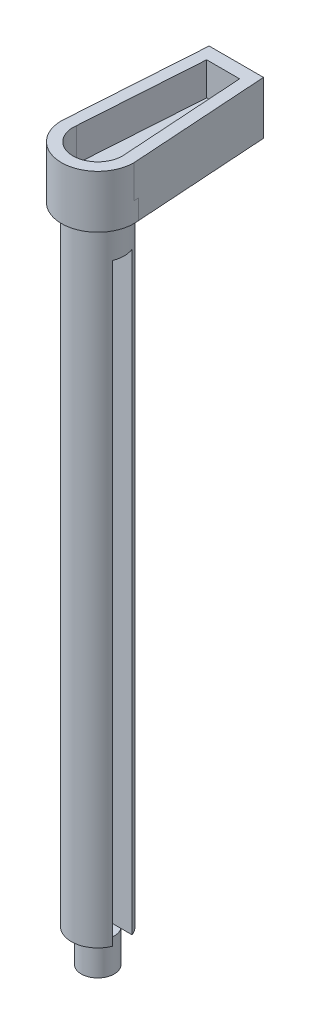
SolidWorks part; units mm, degrees
ref_plane "Front Plane" through (0, 0, 0) normal (0, 0, 1) x (1, 0, 0)
ref_plane "Top Plane" through (0, 0, 0) normal (0, 1, 0) x (1, 0, 0)
ref_plane "Right Plane" through (0, 0, 0) normal (1, 0, 0) x (0, 0, -1)
sketch "Sketch2" plane through (0, 0, 0) normal (0, 0, 1) x (1, 0, 0)
  line L0 (-25, 45) -> (-25, -45)
  line L1 (-25, -45) -> (25, -45)
  line L2 (25, -45) -> (25, 45)
  line L3 (25, 45) -> (-25, 45)
  line L4 (0, 0) -> (0, -45) construction
  line L5 (0, 0) -> (-25, 0) construction
  dimension "D1" = 50
  dimension "D2" = 90
extrude "Boss-Extrude1" add sketch "Sketch2" along normal mid plane 3
sketch "Sketch3" plane through (0, 0, 0) normal (0, -1, 0) x (1, 0, 0)
  line L0 (-25, 1.5) -> (-25, -1.5) construction
  circle A0 centre (-25, 0) radius 4
  point P2 (0, 0)
  point P3 (-26.0976, 0)
  point P4 (0, 0)
  point P5 (-25, 0)
  dimension "D1" = 8
extrude "Boss-Extrude2" add sketch "Sketch3" along normal blind 45 and the other way blind 50
sketch "Sketch4" plane through (0, 50, 0) normal (0, 1, 0) x (1, 0, 0)
  line L0 (-28.75, 0) -> (-27.5, 19)
  line L1 (-27.5, 19) -> (-22.5, 19)
  line L2 (-22.5, 19) -> (-21.25, 0)
  line L3 (-25, 0) -> (-25, 19) construction
  line L4 (-30.5, 0) -> (-29.1184, 21)
  line L5 (-29.1184, 21) -> (-20.8816, 21)
  line L6 (-20.8816, 21) -> (-19.5, 0)
  circle A0 centre (-25, 0) radius 3.75
  circle A1 centre (-25, 0) radius 5.5
  dimension "D2" = 7.5
  dimension "D4" = 11
  dimension "D1" = 19
  dimension "D3" = 5
  dimension "D5" = 2
extrude "Boss-Extrude3" add sketch "Sketch4" along normal blind 3
sketch "Sketch5" plane through (0, 53, -53) normal (0, -1, 0) x (1, 0, 0)
  line L0 (-28.75, 53) -> (-27.5, 34)
  line L1 (-27.5, 34) -> (-22.5, 34)
  line L2 (-22.5, 34) -> (-21.25, 53)
  line L3 (-25, 53) -> (-25, 34) construction
  line L4 (-30.5, 53) -> (-29.1184, 32)
  line L5 (-29.1184, 32) -> (-20.8816, 32)
  line L6 (-20.8816, 32) -> (-19.5, 53)
  line L8 (-29.1184, 32) -> (-20.8816, 32) construction
  circle A0 centre (-25, 53) radius 3.75
  circle A1 centre (-25, 53) radius 5.5
  arc A2 (-19.5474, 52.2794) -> (-30.4526, 52.2794) centre (-25, 53) ccw construction
  line M17 (-29.1184, 32) -> (-30.4526, 52.2794)
  arc M18 (-30.4526, 52.2794) -> (-19.5474, 52.2794) centre (-25, 53) cw
  line M19 (-19.5474, 52.2794) -> (-20.8816, 32)
  line M20 (-20.8816, 32) -> (-29.1184, 32)
  dimension "D2" = 7.5
  dimension "D4" = 11
  dimension "D1" = 2
  dimension "D3" = 5
extrude "Boss-Extrude4" add sketch "Sketch5" against normal blind 5 contours A1 L4 L2 A0 L0 M18 M19 | A1 L0 L1 L2 L6 M17 M20
sketch "Sketch6" plane through (25, 0, 0) normal (1, 0, 0) x (0, 0, -1)
  line L1 (-1.5, 45) -> (1.5, 45)
  line L2 (-1.5, 45) -> (-1.5, -45)
  line L3 (-1.5, -45) -> (1.5, -45)
  line L4 (1.5, 45) -> (1.5, -45)
  line L5 (-1.5, 45) -> (1.5, -45) construction
  line L6 (-1.5, -45) -> (1.5, 45) construction
  point P0 (0, 0)
extrude "Cut-Extrude1" cut sketch "Sketch6" against normal blind 50
sketch "Sketch7" plane through (0, -45, 0) normal (0, -1, 0) x (1, 0, 0)
  line L0 (-25, 4) -> (-25, -4) construction
  arc A0 (-21.2919, 1.5) -> (-21.2919, -1.5) centre (-25, 0) ccw construction
  circle A1 centre (-25, 0) radius 4 construction
  circle A2 centre (-25, 0) radius 2.5
  point P10 (0, 0)
  dimension "D1" = 5
extrude "Boss-Extrude5" add sketch "Sketch7" along normal blind 5
